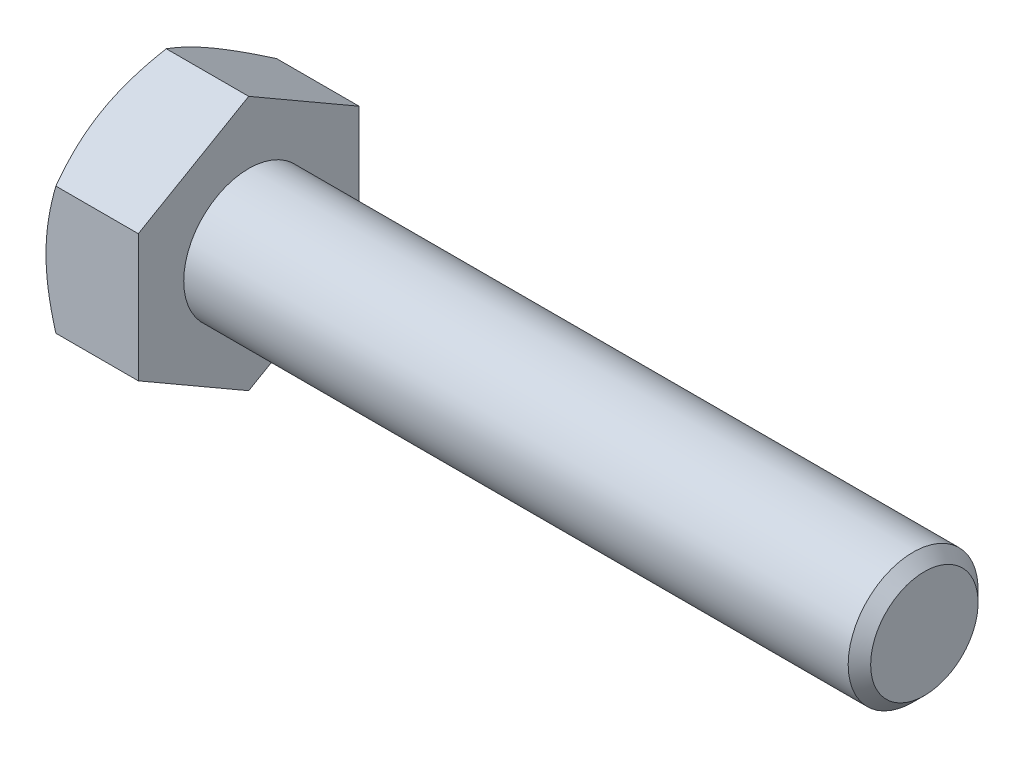
SolidWorks part; units mm, degrees
extrude "BaseHead" add sketch "Sketch1" along normal blind 11.2776
sketch "Sketch1" plane through (0, 0, 0) normal (1, 0, 0) x (0, 0, -1)
  line L0 (13.4874, 7.787) -> (13.4874, -7.787)
  line L1 (-13.4874, 7.787) -> (-13.4874, -7.787)
  line L2 (13.4874, -7.787) -> (0, -15.5739)
  line L3 (0, -15.5739) -> (-13.4874, -7.787)
  line L4 (13.4874, 7.787) -> (0, 15.5739)
  line L5 (0, 15.5739) -> (-13.4874, 7.787)
  dimension "Width_flats" = 26.9748
  dimension "D2" = 120
  dimension "D3" = 13.4874
  dimension "D4" = 13.4874
  dimension "D5" = 13.4874
ref_plane "Plane1" through (0, 0, 0) normal (0, 0, 1) x (1, 0, 0)
ref_plane "Plane2" through (0, 0, 0) normal (0, 1, 0) x (1, 0, 0)
ref_plane "Plane3" through (0, 0, 0) normal (1, 0, 0) x (0, 0, -1)
sketch "BodySke" plane through (0, 0, 0) normal (0, 0, 1) x (1, 0, 0)
  line L0 (0, 7.787) -> (0, -7.787) construction
  line L1 (0, 0) -> (93.8276, 0)
  line L2 (0, 0) -> (0, 7.9375)
  line L3 (0, 7.9375) -> (92.4535, 7.9375)
  line L4 (93.8276, 0) -> (93.8276, 6.5634)
  line L5 (11.2776, 15.5739) -> (11.2776, 7.787) construction
  line L6 (93.8276, 6.5634) -> (92.4535, 7.9375)
  line L7 (0, 0) -> (96.52, 0) construction
  line L8 (93.8276, -6.5634) -> (92.4535, -7.9375) construction
  line L9 (0, -7.9375) -> (92.4535, -7.9375) construction
  line L10 (13.5865, 15.24) -> (13.5865, -3.81) construction
  line L11 (62.0776, 15.24) -> (62.0776, -3.81) construction
  line L12 (11.2776, 7.787) -> (11.2776, -7.787) construction
  dimension "Diameter" = 15.875
revolve "BaseBody" add sketch "BodySke" angle 360 about L7
cosmetic thread "ThreadCosmetic" [suppressed] parameters "Thread_length"=31.75, "Thread_minor"=13.1267
sketch "Sketch3" plane through (0, 0, 0) normal (0, 0, 1) x (1, 0, 0)
  line L0 (0, 13.4874) -> (4.8708, 21.9239)
  line L1 (0, 15.5739) -> (0, 7.787) construction
  line L2 (4.8708, 21.9239) -> (4.8708, 28.2739)
  line L3 (4.8708, 28.2739) -> (-12.7, 28.2739)
  line L4 (-12.7, 28.2739) -> (-12.7, 13.4874)
  line L5 (-12.7, 13.4874) -> (0, 13.4874)
  line L6 (0, 0) -> (99.06, 0) construction
  line L7 (11.2776, 15.5739) -> (0, 15.5739) construction
  dimension "D1" = 13.4874
  dimension "D2" = 6.35
  dimension "D3" = 12.7
  dimension "D4" = 6.35
  dimension "Head_ch_ang" = 30
revolve "HeadChamfer" cut sketch "Sketch3" angle 360 about L6
fillet "HeadFillet" [suppressed] radius 1.524
sketch "ThdSchSke" plane through (0, 0, 0) normal (0, 0, 1) x (1, 0, 0)
  line L0 (62.0776, -6.5634) -> (61.1154, -7.9375)
  line L1 (62.0776, -6.5634) -> (63.0398, -7.9375)
  line L2 (63.0398, -7.9375) -> (63.0398, -9.9219)
  line L3 (-3.175, 0) -> (5.1513, 0) construction
  line L5 (63.0398, -9.9219) -> (61.1154, -9.9219)
  line L6 (61.1154, -9.9219) -> (61.1154, -7.9375)
  dimension "Thread_minor" = 13.1267
  dimension "Diameter" = 15.875
revolve "ThreadSchematic" [suppressed] cut sketch "ThdSchSke" angle 360 about L3
pattern_linear "ThdSchPat" [suppressed]
equation "\"D3@Sketch1\" = \"Width_flats@Sketch1\" / 2"
equation "\"D4@Sketch1\" = \"D3@Sketch1\""
equation "\"D5@Sketch1\" = \"D4@Sketch1\""
equation "\"Thread_minor@ThreadCosmetic\" = \"Minor_dia@BodySke\""
equation "\"D1@Sketch3\" = \"Width_flats@Sketch1\" / 2"
equation "\"Thread_length@ThreadCosmetic\" = ((sgn( (\"Length@BodySke\" - \"Advance@BodySke\" ) - \"Thread_nom@BodySke\" )-1)*( (\"Length@BodySke\" - \"Advance@BodySke\" ) - \"Thread_nom@BodySke\" ))/-2+ \"Thread_nom@BodySke\""
equation "\"Thread_minor@ThdSchSke\" = \"Minor_dia@BodySke\""
equation "\"Diameter@ThdSchSke\" = \"Diameter@BodySke\""
equation "\"Overcut@ThdSchSke\" = \"Diameter@BodySke\" * 1.25"
equation "\"Start@ThdSchSke\" = \"Head_ht@BaseHead\" + \"Length@BodySke\" - \"Thread_length@ThreadCosmetic\"  '---Non-countersunk---"
equation "\"Num_threads@ThdSchPat\" = int( \"Thread_length@ThreadCosmetic\" / \"Advance@BodySke\" + 0.999 )  + 1"
equation "\"Advance@ThdSchPat\" = \"Thread_length@ThreadCosmetic\" /  (\"Num_threads@ThdSchPat\" - 1) 'relax it"
equation "\"Num_threads@ThdSchPat\" = \"Num_threads@ThdSchPat\" - sgn( \"Num_threads@ThdSchPat\" - 1) '---chamfered tips only---"
